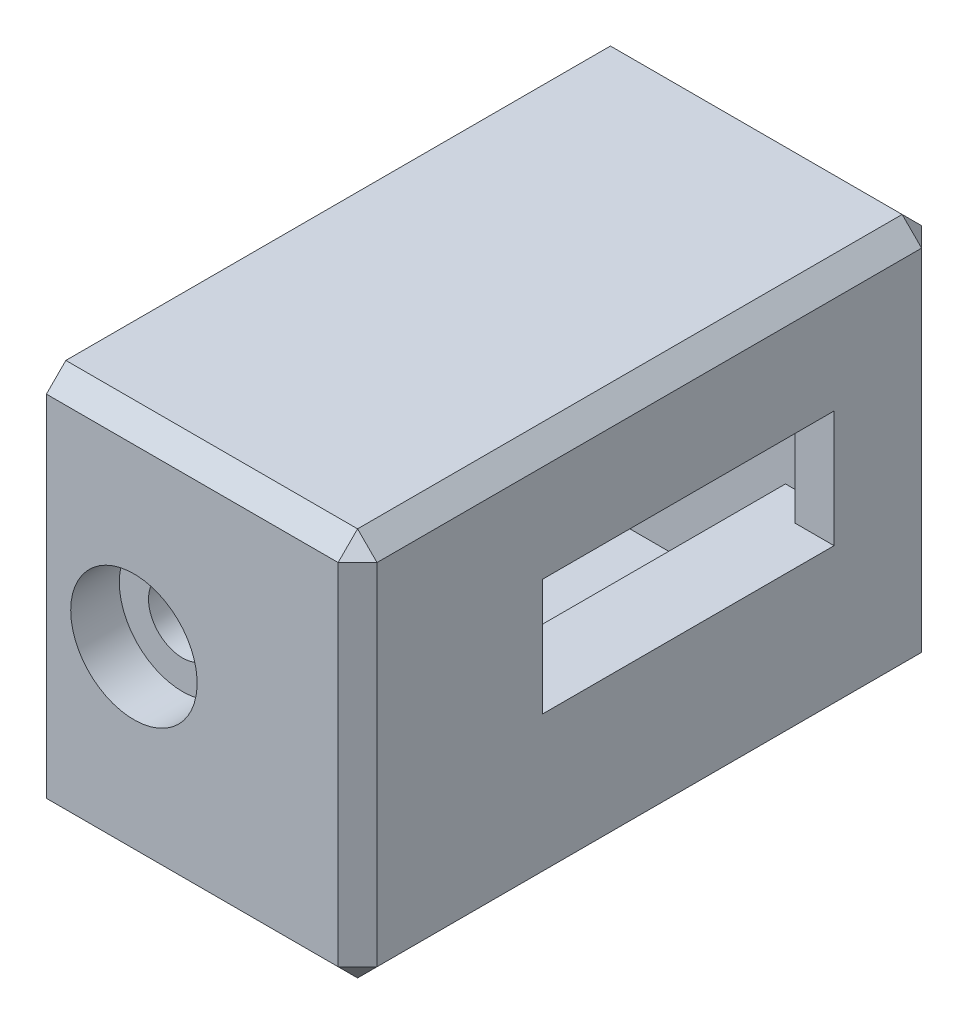
SolidWorks part; units mm, degrees
material "Hot Galvanized Steel"
ref_plane "Front" through (0, 0, 0) normal (0, 0, 1) x (1, 0, 0)
ref_plane "Top" through (0, 0, 0) normal (0, 1, 0) x (1, 0, 0)
ref_plane "Right" through (0, 0, 0) normal (1, 0, 0) x (0, 0, -1)
sketch "Sketch1" plane through (0, 0, 0) normal (0, 0, 1) x (1, 0, 0)
  line L1 (-8, 10) -> (8, 10)
  line L2 (-8, 10) -> (-8, -10)
  line L3 (-8, -10) -> (8, -10)
  line L4 (8, 10) -> (8, -10)
  line L5 (-8, 10) -> (8, -10) construction
  line L6 (-8, -10) -> (8, 10) construction
  point P0 (0, 0)
  dimension "D1" = 20
  dimension "D2" = 16
extrude "Boss-Extrude1" add sketch "Sketch1" along normal mid plane 30
shell "Shell1" thickness 2
sketch "Sketch10" plane through (6, 0, 0) normal (-1, 0, 0) x (0, 0, 1)
  line L0 (13, -8) -> (-13, -8) construction
  line L1 (-13, 8) -> (-11, 8)
  line L2 (-13, 8) -> (-13, -8)
  line L3 (-13, -8) -> (-11, -8)
  line L4 (-11, 8) -> (-11, -8)
  line L6 (13, 8) -> (11, 8)
  line L7 (13, 8) -> (13, -8)
  line L8 (13, -8) -> (11, -8)
  line L9 (11, 8) -> (11, -8)
  dimension "D1" = 22
extrude "Boss-Extrude4" add sketch "Sketch10" along normal up to surface (14 mm away) up to face at (-8, 0, 0)
sketch "Sketch3" plane through (8, 0, 9.25) normal (-1, 0, 0) x (0, 0, 1)
  line L1 (-18.75, 4) -> (-3.75, 4)
  line L2 (-18.75, 4) -> (-18.75, -2)
  line L3 (-18.75, -2) -> (-3.75, -2)
  line L4 (-3.75, 4) -> (-3.75, -2)
  line L5 (-18.75, 4) -> (-3.75, -2) construction
  line L6 (-18.75, -2) -> (-3.75, 4) construction
  point P0 (-11.25, 1)
  dimension "D1" = 15
  dimension "D2" = 2
  dimension "D3" = 6
  dimension "D4" = 1
extrude "Cut-Extrude2" cut sketch "Sketch3" along normal up to next
chamfer "Chamfer1" distance 1 angle 45 8 edges at (0, -10, 15) (0, -10, -15) (0, 10, 15) (0, 10, -15) (8, 0, -15) (8, -10, 0) (8, 0, 15) (8, 10, 0)
sketch "Sketch4" plane through (6, 0, 0) normal (-1, 0, 0) x (0, 0, 1)
  line L0 (5.5, 4) -> (-9.5, 4) construction
  line L1 (-11, 8) -> (-7, 8)
  line L2 (-11, 8) -> (-11, 4)
  line L3 (-11, 4) -> (-7, 4)
  line L4 (-7, 8) -> (-7, 4)
  line L6 (11, 8) -> (7, 8)
  line L7 (11, 8) -> (11, 4)
  line L8 (11, 4) -> (7, 4)
  line L9 (7, 8) -> (7, 4)
  line L10 (-11, -3.5) -> (11, -3.5)
  line L11 (-11, -3.5) -> (-11, -2)
  line L12 (-11, -2) -> (11, -2)
  line L13 (11, -3.5) -> (11, -2)
  line L15 (-9.5, -2) -> (5.5, -2) construction
  line L16 (-11, 8) -> (-11, -8) construction
  line L17 (11, 8) -> (11, -8) construction
  dimension "D1" = 1.5
extrude "Boss-Extrude2" add sketch "Sketch4" along normal blind 2
sketch "Sketch5" plane through (0, -10, 0) normal (0, -1, 0) x (1, 0, 0)
  line L0 (-8, 14) -> (-8, -14) construction
  line L1 (-8, -0.5) -> (4, -0.5)
  line L2 (-8, -0.5) -> (-8, 11)
  line L3 (-8, 11) -> (4, 11)
  line L4 (4, -0.5) -> (4, 11)
  line L5 (8, 14) -> (8, -14) construction
  line L6 (-8, 15) -> (7, 15) construction
  dimension "D1" = 4
  dimension "D2" = 11.5
  dimension "D3" = 4
extrude "Cut-Extrude3" cut sketch "Sketch5" against normal up to next
chamfer "Chamfer2" [suppressed] distance 1 angle 45
sketch "Sketch6" [suppressed] plane through (-5, 0, 0) normal (-1, 0, 0) x (0, 0, 1)
  line L1 (-10.5, 7.5) -> (10.5, 7.5)
  line L2 (-10.5, 7.5) -> (-10.5, -7.5)
  line L3 (-10.5, -7.5) -> (10.5, -7.5)
  line L4 (10.5, 7.5) -> (10.5, -7.5)
  line L5 (-10.5, 7.5) -> (10.5, -7.5) construction
  line L6 (-10.5, -7.5) -> (10.5, 7.5) construction
  line L34 (-14, -10) -> (14, -10)
  line L35 (14, -10) -> (15, -9)
  line L36 (15, -9) -> (15, 9)
  line L38 (15, 9) -> (14, 10)
  line L40 (14, 10) -> (-14, 10)
  line L41 (-14, 10) -> (-15, 9)
  line L42 (-15, 9) -> (-15, -9)
  line L43 (-15, -9) -> (-14, -10)
  line L44 (-14, -10) -> (14, -10)
  line L45 (14, -10) -> (15, -9)
  line L46 (15, -9) -> (15, 9)
  line L47 (15, 9) -> (14, 10)
  line L48 (14, 10) -> (-14, 10)
  line L49 (-14, 10) -> (-15, 9)
  line L50 (-15, 9) -> (-15, -9)
  line L51 (-15, -9) -> (-14, -10)
  point P2 (0, 0)
  dimension "D1" = 2.5
  dimension "D3" = 4.5
  dimension "D2" = 0
extrude "Cut-Extrude4" [suppressed] cut sketch "Sketch6" against normal blind 8
sketch "Sketch7" [suppressed] plane through (3, 0, 0) normal (-1, 0, 0) x (0, 0, 1)
  line L0 (-14, -10) -> (14, -10) construction
  line L1 (0, -7.5) -> (-10.5, -7.5)
  line L2 (0, -7.5) -> (0, -10)
  line L3 (0, -10) -> (-10.5, -10)
  line L4 (-10.5, -7.5) -> (-10.5, -10)
  dimension "D1" = 10.5
extrude "Boss-Extrude3" [suppressed] add sketch "Sketch7" along normal up to surface (8 mm away)
sketch "Sketch8" plane through (0, 0, -15) normal (0, 0, -1) x (-1, 0, 0)
  line L0 (8, 9) -> (8, -9) construction
  circle A0 centre (3.5, 0) radius 1.75
  dimension "D1" = 3.5
  dimension "D2" = 4.5
extrude "Cut-Extrude5" cut sketch "Sketch8" against normal through all
sketch "Sketch9" plane through (0, 0, -15) normal (0, 0, -1) x (-1, 0, 0)
  circle A0 centre (3.5, 0) radius 3.25
  dimension "D1" = 6.5
extrude "Cut-Extrude6" cut sketch "Sketch9" against normal blind 2.5
mirror "Mirror1" about plane through (0, 0, 0) normal (0, 0, 1) of "Cut-Extrude6"
sketch "Sketch11" [suppressed] plane through (0, 0, 10.5) normal (0, 0, 1) x (1, 0, 0)
  line L0 (3, -7.5) -> (3, 7.5) construction
  circle A0 centre (-1.5, 0) radius 1.25
  dimension "D1" = 2.5
  dimension "D2" = 4.5
extrude "Cut-Extrude7" [suppressed] cut sketch "Sketch11" against normal blind 8
mirror "Mirror2" [suppressed] about plane through (0, 0, 0) normal (0, 0, 1)
